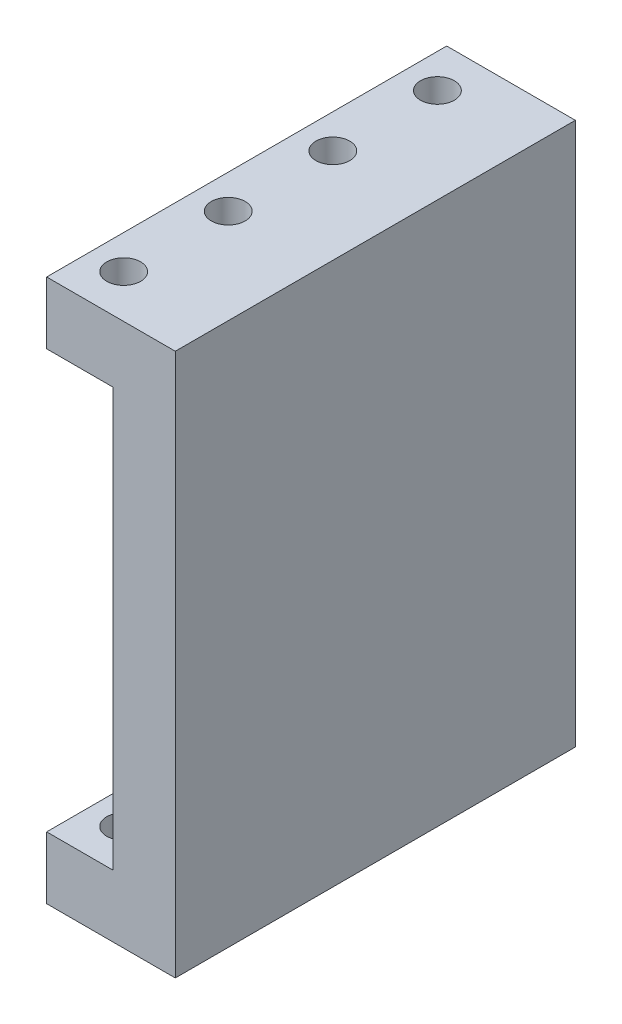
SolidWorks part; units mm, degrees
material "ABS"
ref_plane "Front Plane" through (0, 0, 0) normal (0, 0, 1) x (1, 0, 0)
ref_plane "Top Plane" through (0, 0, 0) normal (0, 1, 0) x (1, 0, 0)
ref_plane "Right Plane" through (0, 0, 0) normal (1, 0, 0) x (0, 0, -1)
sketch "Sketch1" plane through (0, 0, 0) normal (0, 0, 1) x (1, 0, 0)
  line L0 (-4.7625, 0) -> (5.08, 0)
  line L1 (5.08, 0) -> (5.08, -41.529)
  line L2 (5.08, -41.529) -> (-4.7625, -41.529)
  line L3 (-4.7625, -41.529) -> (-4.7625, -36.7665)
  line L4 (-4.7625, -36.7665) -> (0.3175, -36.7665)
  line L5 (0.3175, -36.7665) -> (0.3175, -4.7625)
  line L6 (0.3175, -4.7625) -> (-4.7625, -4.7625)
  line L7 (-4.7625, -4.7625) -> (-4.7625, 0)
  dimension "D7" = 5.08
  dimension "D1" = 4.7625
  dimension "D2" = 41.529
  dimension "D3" = 9.8425
  dimension "D4" = 4.7625
  dimension "D5" = 5.08
  dimension "D6" = 32.004
extrude "Boss-Extrude1" add sketch "Sketch1" along normal blind 30.607
sketch "Sketch2" plane through (0, 0, 0) normal (0, 1, 0) x (1, 0, 0)
  line L0 (0.3175, -30.607) -> (0.3175, 0) construction
  line L1 (5.08, -30.607) -> (-4.7625, -30.607) construction
  line L2 (5.08, 0) -> (-4.7625, 0) construction
  line L3 (5.08, -30.607) -> (5.08, 0) construction
  line L4 (-4.7625, -15.3035) -> (5.08, -15.3035) construction
  line L5 (-4.7625, -30.607) -> (-4.7625, 0) construction
  circle A0 centre (-2.1717, -27.305) radius 1.2954
  circle A1 centre (-2.1717, -19.304) radius 1.2954
  circle A2 centre (-2.1717, -3.302) radius 1.2954
  circle A3 centre (-2.1717, -11.303) radius 1.2954
  dimension "D1" = 2.5908
  dimension "D4" = 2.5908
  dimension "D2" = 4.7625
  dimension "D3" = 2.4892
  dimension "D5" = 8.001
  dimension "D6" = 3.302
  dimension "D7" = 3.302
  dimension "D8" = 2.5908
extrude "Cut-Extrude1" cut sketch "Sketch2" against normal through all
ref_plane "Plane1" [suppressed] through (-15.6718, 0, 0) normal (1, 0, 0) x (0, 0, -1)
